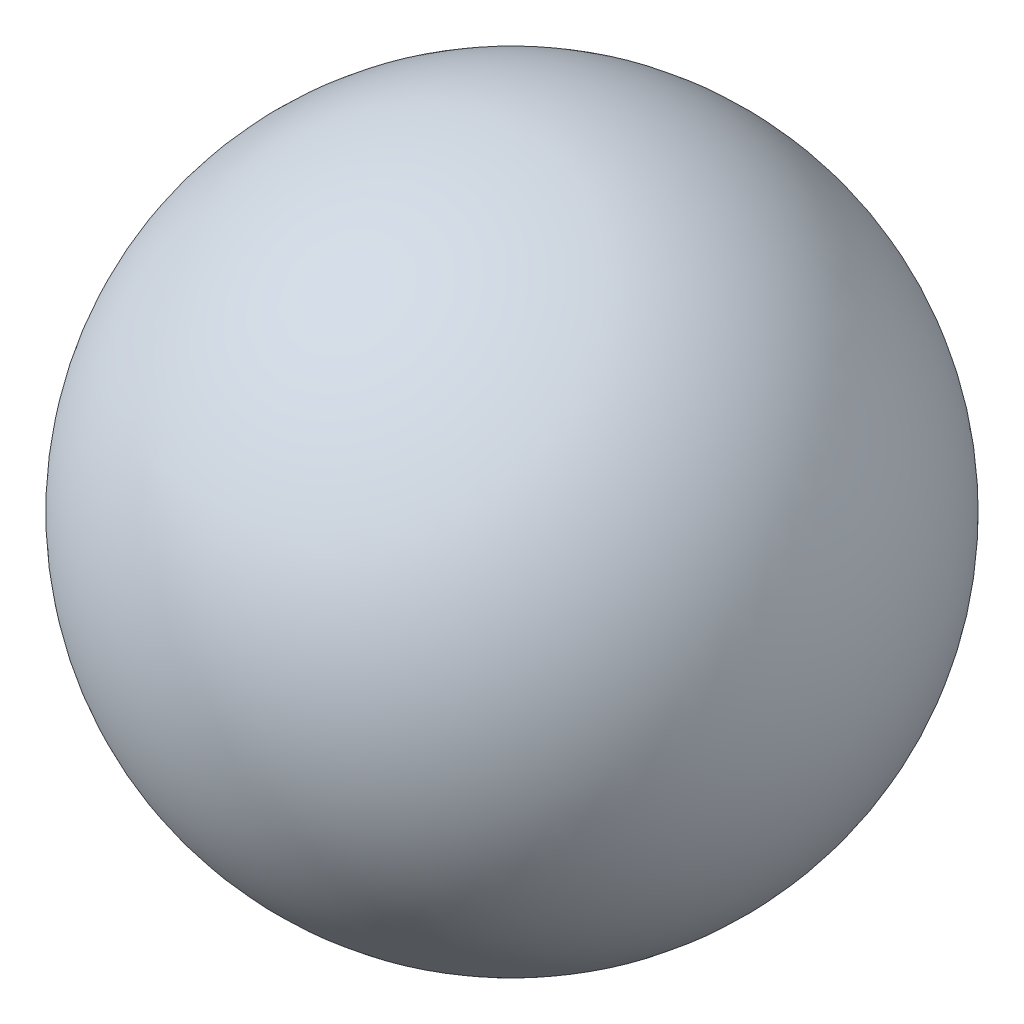
SolidWorks part; units mm, degrees
ref_plane "Front Plane" through (0, 0, 0) normal (0, 0, 1) x (1, 0, 0)
ref_plane "Top Plane" through (0, 0, 0) normal (0, 1, 0) x (1, 0, 0)
ref_plane "Right Plane" through (0, 0, 0) normal (1, 0, 0) x (0, 0, -1)
sketch "Sketch1" plane through (0, 0, 0) normal (0, 0, 1) x (1, 0, 0)
  line L0 (0, 0) -> (0, 1739.5986) construction
  line L1 (0, 786.18) -> (0, 785)
  line L2 (0, -785) -> (0, -786.18)
  arc A2 (0, 785) -> (0, -785) centre (0, 0) ccw
  arc A3 (0, 786.18) -> (0, -786.18) centre (0, 0) ccw
revolve "Revolve3" add sketch "Sketch1" angle 360 about L0
